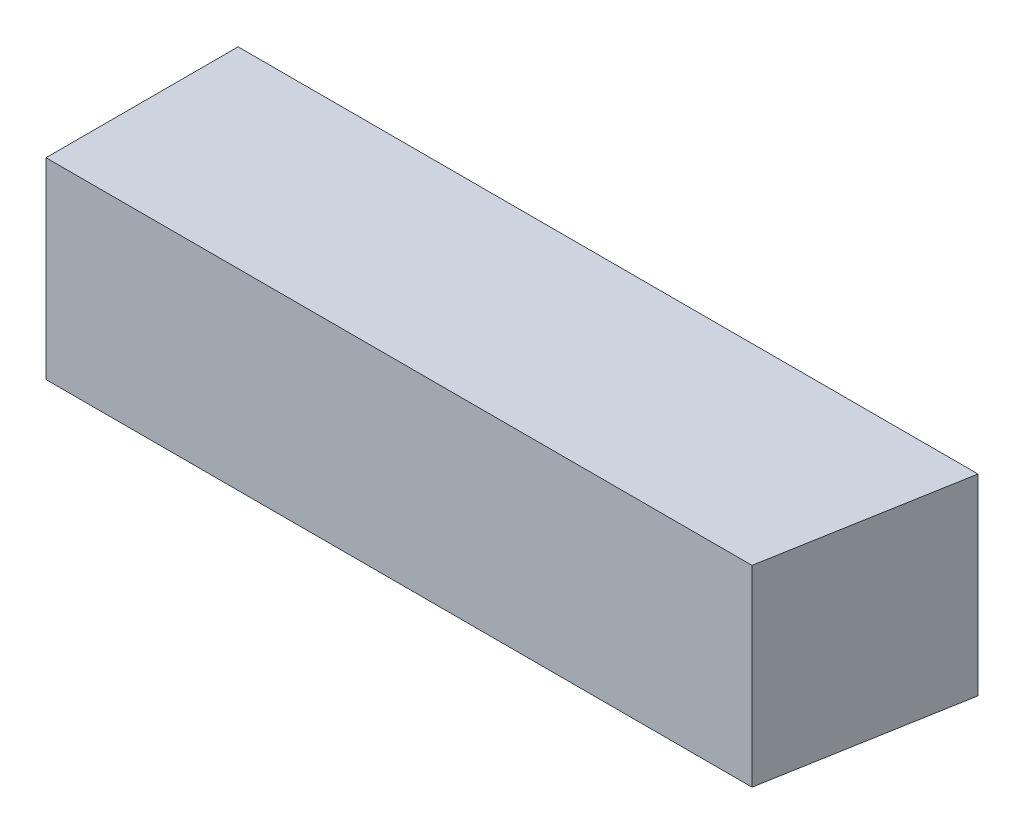
SolidWorks part; units mm, degrees
ref_plane "Front Plane" through (0, 0, 0) normal (1, 0, 0) x (0, 1, 0)
ref_plane "Top Plane" through (0, 0, 0) normal (0, 0, 1) x (0, 1, 0)
ref_plane "Right Plane" through (0, 0, 0) normal (0, 1, 0) x (-1, 0, 0)
sketch "Sketch1" plane through (0, 0, 0) normal (1, 0, 0) x (0, 1, 0)
  line L1 (0, 0) -> (88.9, 0)
  line L2 (0, 0) -> (0, 88.9)
  line L3 (0, 88.9) -> (88.9, 88.9)
  line L4 (88.9, 0) -> (88.9, 88.9)
  dimension "D1" = 88.9
  dimension "D2" = 88.9
extrude "Boss-Extrude1" add sketch "Sketch1" along normal blind 342.392
sketch "Sketch2" plane through (0, 0, 0) normal (0, 1, 0) x (-1, 0, 0)
  line L0 (-342.392, 0) -> (-326.7189, 88.9)
  line L1 (-342.392, 88.9) -> (0, 88.9) construction
  line L2 (-326.7189, 88.9) -> (-342.392, 88.9)
  line L3 (-342.392, 88.9) -> (-342.392, 0)
  dimension "D1" = 15.6731
extrude "Cut-Extrude1" cut sketch "Sketch2" along normal blind 88.9
